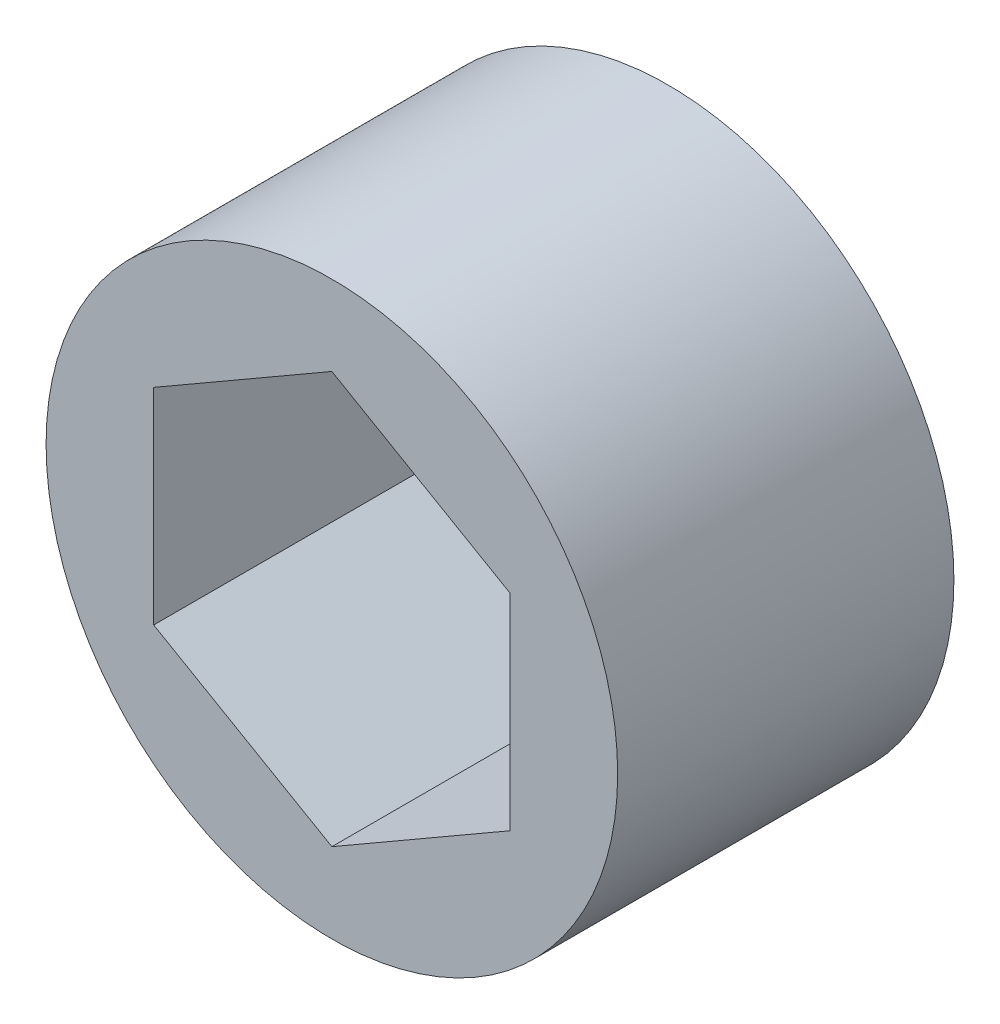
SolidWorks part; units mm, degrees
material "Nylon 101"
ref_plane "Front Plane" through (0, 0, 0) normal (0, 0, 1) x (1, 0, 0)
ref_plane "Top Plane" through (0, 0, 0) normal (0, 1, 0) x (1, 0, 0)
ref_plane "Right Plane" through (0, 0, 0) normal (1, 0, 0) x (0, 0, -1)
sketch "Sketch1" plane through (0, 0, 0) normal (0, 0, 1) x (1, 0, 0)
  line L1 (0, 7.7723) -> (-6.731, 3.8861)
  line L2 (-6.731, 3.8861) -> (-6.731, -3.8861)
  line L3 (-6.731, -3.8861) -> (0, -7.7723)
  line L4 (0, -7.7723) -> (6.731, -3.8861)
  line L5 (6.731, -3.8861) -> (6.731, 3.8861)
  line L6 (6.731, 3.8861) -> (0, 7.7723)
  circle A0 centre (0, 0) radius 6.731 construction
  circle A1 centre (0, 0) radius 10.795
  dimension "D1" = 13.462
  dimension "D2" = 21.59
extrude "Boss-Extrude1" add sketch "Sketch1" along normal blind 12.7
